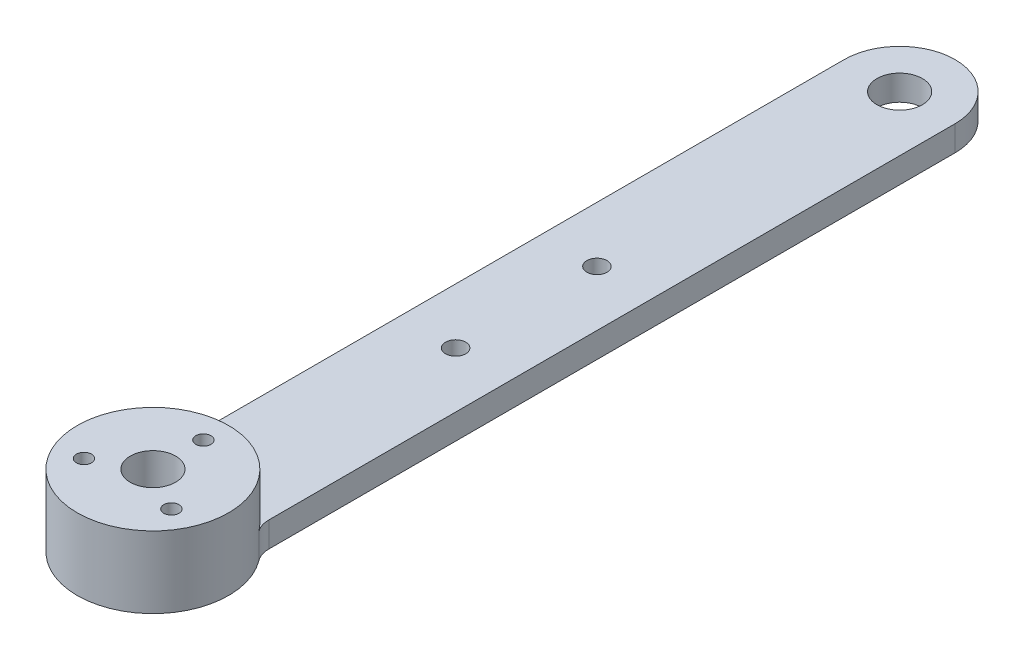
SolidWorks part; units mm, degrees
ref_plane "前视基准面" through (0, 0, 0) normal (0, 0, 1) x (1, 0, 0)
ref_plane "上视基准面" through (0, 0, 0) normal (0, 1, 0) x (1, 0, 0)
ref_plane "右视基准面" through (0, 0, 0) normal (1, 0, 0) x (0, 0, -1)
sketch "草图1" plane through (0, 0, 0) normal (0, 1, 0) x (1, 0, 0)
  line L0 (-67.5371, 79.1703) -> (-67.5371, -56.8297)
  line L5 (-45.5371, 79.1703) -> (-45.5371, -56.8297)
  arc A0 (-45.5371, 79.1703) -> (-67.5371, 79.1703) centre (-56.5371, 79.1703) ccw
  circle A1 centre (-56.5371, 79.1703) radius 4.5
  circle A2 centre (-56.5371, 19.1703) radius 2
  circle A3 centre (-56.5371, -8.8297) radius 2
  arc A4 (-68.5371, -59.8297) -> (-44.5371, -59.8297) centre (-56.5371, -68.8297) ccw
  circle A6 centre (-56.5371, -68.8297) radius 4.5
  circle A7 centre (-65.1974, -73.8297) radius 1.5
  circle A8 centre (-47.8769, -73.8297) radius 1.5
  circle A9 centre (-56.5371, -58.8297) radius 1.5
  arc A10 (-67.5371, -56.8297) -> (-68.5371, -59.8297) centre (-72.5371, -56.8297) cw
  arc A11 (-45.5371, -56.8297) -> (-44.5371, -59.8297) centre (-40.5371, -56.8297) ccw
  dimension "D1" = 5
  dimension "D2" = 5
  dimension "D3" = 11
  dimension "D4" = 60
  dimension "D5" = 28
extrude "凸台-拉伸1" add sketch "草图1" along normal blind 5
sketch "草图2" plane through (0, 5, 0) normal (0, 1, 0) x (1, 0, 0)
  circle A0 centre (-56.5371, -68.8297) radius 15
  circle A1 centre (-65.1974, -73.8297) radius 1.5
  circle A2 centre (-56.5371, -58.8297) radius 1.5
  circle A3 centre (-47.8769, -73.8297) radius 1.5
  circle A4 centre (-56.5371, -68.8297) radius 4.5
extrude "凸台-拉伸3" add sketch "草图2" along normal blind 9.2
